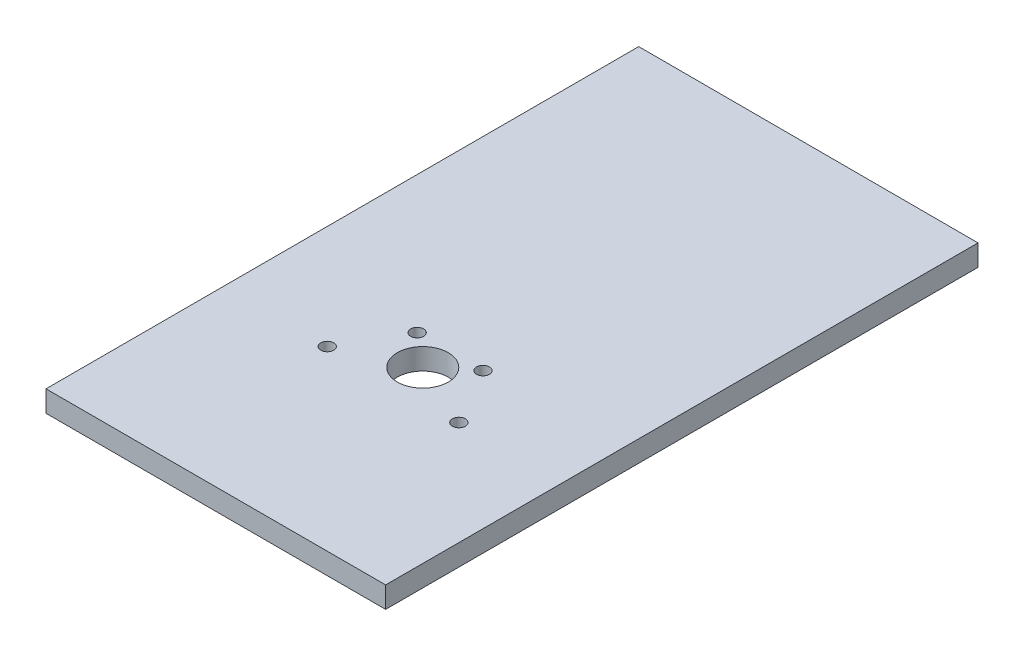
SolidWorks part; units mm, degrees
ref_plane "Front Plane" through (0, 0, 0) normal (0, 0, 1) x (1, 0, 0)
ref_plane "Top Plane" through (0, 0, 0) normal (0, 1, 0) x (1, 0, 0)
ref_plane "Right Plane" through (0, 0, 0) normal (1, 0, 0) x (0, 0, -1)
sketch "Sketch1" plane through (0, 0, 0) normal (0, 1, 0) x (1, 0, 0)
  line L0 (0, -40.3795) -> (80, -40.4673)
  line L2 (0, -40.3795) -> (0, -180)
  line L3 (0, -180) -> (80, -180)
  line L4 (80, -40.4673) -> (80, -180)
  line L5 (40, -90) -> (80, -180) construction
  line L6 (80, -180) -> (78.043, -177.852) construction
  line L7 (60, -135) -> (40, -180) construction
  line L9 (40, -90) -> (40, -174.4486) construction
  circle A0 centre (40, -131.25) radius 6
  circle A1 centre (24.5, -138.25) radius 1.525
  circle A2 centre (55.5, -138.25) radius 1.525
  circle A3 centre (32.25, -124.8266) radius 1.525
  circle A4 centre (47.75, -124.8266) radius 1.525
extrude "Boss-Extrude1" add sketch "Sketch1" along normal blind 5
